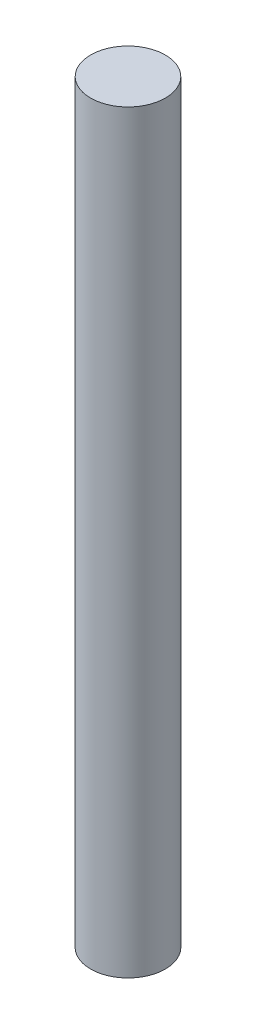
SolidWorks part; units mm, degrees
material "Plain Carbon Steel"
ref_plane "Front Plane" through (0, 0, 0) normal (0, 0, 1) x (1, 0, 0)
ref_plane "Top Plane" through (0, 0, 0) normal (0, 1, 0) x (1, 0, 0)
ref_plane "Right Plane" through (0, 0, 0) normal (1, 0, 0) x (0, 0, -1)
sketch "Sketch1" plane through (0, 0, 0) normal (0, 1, 0) x (1, 0, 0)
  circle A0 centre (0, 0) radius 5
  dimension "D1" = 10
extrude "Boss-Extrude1" add sketch "Sketch1" along normal blind 100.96
